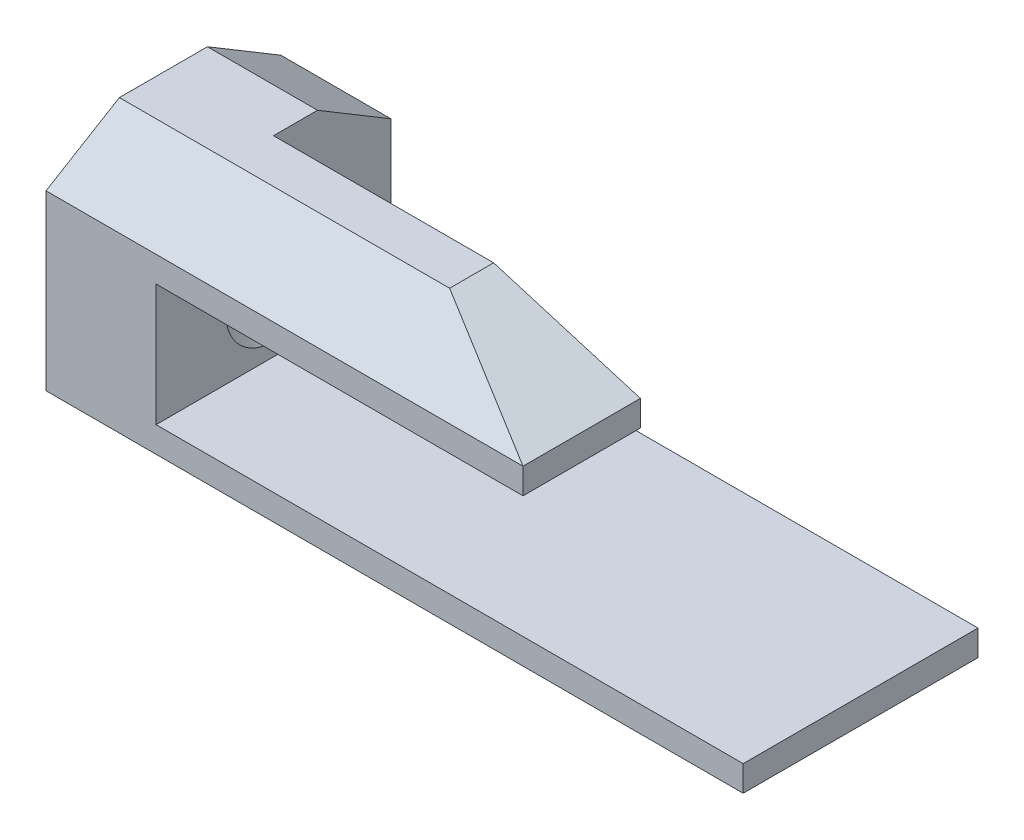
SolidWorks part; units mm, degrees
ref_plane "Спереди" through (0, 0, 0) normal (0, 0, 1) x (1, 0, 0)
ref_plane "Сверху" through (0, 0, 0) normal (0, 1, 0) x (1, 0, 0)
ref_plane "Справа" through (0, 0, 0) normal (1, 0, 0) x (0, 0, -1)
sketch "Эскиз2" plane through (0, 0, 0) normal (0, 0, 1) x (1, 0, 0)
  line L0 (0, 0) -> (65, 0)
  line L1 (65, 0) -> (65, -6)
  line L2 (65, -6) -> (15, -6)
  line L3 (15, -6) -> (15, -22.6)
  line L4 (15, -22.6) -> (95, -22.6)
  line L5 (95, -22.6) -> (95, -28.6)
  line L6 (95, -28.6) -> (0, -28.6)
  line L7 (0, -28.6) -> (0, 0)
  dimension "D1" = 15
  dimension "D2" = 80
  dimension "D3" = 50
  dimension "D4" = 6
  dimension "D5" = 16.6
  dimension "D6" = 6
  dimension "D7" = 65
  dimension "D8" = 95
  dimension "D9" = 28.6
extrude "Бобышка-Вытянуть1" add sketch "Эскиз2" along normal blind 32
sketch "Эскиз3" plane through (0, 0, 0) normal (-1, 0, 0) x (0, 0, 1)
  line L0 (0, 0) -> (32, -28.6) construction
  line L1 (32, -28.6) -> (0, -28.6) construction
  line L2 (32, 0) -> (32, -28.6) construction
  line L3 (32, 0) -> (0, -28.6) construction
  line L4 (32, 0) -> (0, 0) construction
  line L5 (0, -14.3) -> (32, -14.3) construction
  line L6 (0, 0) -> (0, -28.6) construction
  line L7 (16, 0) -> (16, -28.6) construction
  line L9 (5.3934, -14.3) -> (16, -24.9066)
  line L10 (16, -24.9066) -> (26.6066, -14.3)
  line L11 (26.6066, -14.3) -> (16, -3.6934)
  line L12 (16, -3.6934) -> (5.3934, -14.3)
  circle A0 centre (16, -14.3) radius 7.5 construction
  dimension "D1" = 15
extrude "Вырез-Вытянуть2" cut sketch "Эскиз3" against normal blind 3
sketch "Эскиз4" plane through (0, 0, 0) normal (-1, 0, 0) x (0, 0, 1)
  line L0 (16, 0) -> (16, -28.6) construction
  line L1 (32, 0) -> (0, 0) construction
  line L2 (32, -28.6) -> (0, -28.6) construction
  line L3 (32, -14.3) -> (0, -14.3) construction
  line L4 (32, 0) -> (32, -28.6) construction
  line L5 (0, 0) -> (0, -28.6) construction
  circle A0 centre (16, -14.3) radius 2.5
  dimension "D1" = 5
extrude "Вырез-Вытянуть3" cut sketch "Эскиз4" against normal up to surface (15 mm away) up to face at (15, -14.3, 16)
chamfer "Фаска2" distance 4 angle 45 1 edges at (15, -16.8, 16)
sketch "Эскиз6" plane through (65, 0, 0) normal (1, 0, 0) x (0, 0, -1)
  line L2 (-32, 0) -> (0, 0) construction
  line L3 (-16, 0) -> (-22, 0)
  line L4 (-16, 0) -> (-16, 3.5)
  line L5 (-16, 3.5) -> (-22, 3.5)
  line L6 (-22, 0) -> (-22, 3.5)
  line L7 (-32, -6) -> (0, -6) construction
  dimension "D1" = 6
  dimension "D2" = 9.5
extrude "Бобышка-Вытянуть2" add sketch "Эскиз6" against normal up to surface (50 mm away) up to face at (15, -20.8, 16)
sketch "Эскиз7" plane through (65, 0, 0) normal (1, 0, 0) x (0, 0, -1)
  line L1 (-16, 0) -> (0, 0)
  line L2 (-16, 0) -> (-16, -6)
  line L3 (-16, -6) -> (0, -6)
  line L4 (0, 0) -> (0, -6)
extrude "Вырез-Вытянуть5" cut sketch "Эскиз7" against normal up to surface (50 mm away) up to face at (15, -20.8, 16)
sketch "Эскиз8" plane through (15, 0, 0) normal (-1, 0, 0) x (0, 0, 1)
  line L1 (16, 3.5) -> (22, 3.5)
  line L2 (16, 3.5) -> (16, 0)
  line L3 (16, 0) -> (22, 0)
  line L4 (22, 3.5) -> (22, 0)
extrude "Бобышка-Вытянуть3" add sketch "Эскиз8" along normal up to surface (15 mm away) up to face at (0, -14.3, 16)
sketch "Эскиз9" plane through (0, 0, 16) normal (0, 0, -1) x (-1, 0, 0)
  line L1 (0, 3.5) -> (-15, 3.5)
  line L2 (0, 3.5) -> (0, 0)
  line L3 (0, 0) -> (-15, 0)
  line L4 (-15, 3.5) -> (-15, 0)
extrude "Бобышка-Вытянуть4" add sketch "Эскиз9" along normal blind 6
sketch "Эскиз10" plane through (0, 0, 0) normal (-1, 0, 0) x (0, 0, 1)
  line L0 (32, -28.6) -> (0, -28.6) construction
  line L1 (16, -28.6) -> (22, -28.6)
  line L2 (16, -28.6) -> (16, -32.1)
  line L3 (16, -32.1) -> (22, -32.1)
  line L4 (22, -28.6) -> (22, -32.1)
  line L6 (16, -32.1) -> (10, -32.1)
  line L7 (16, -32.1) -> (16, -28.6)
  line L8 (16, -28.6) -> (10, -28.6)
  line L9 (10, -32.1) -> (10, -28.6)
  line M10 (0, -28.6) -> (32, -28.6)
  dimension "D1" = 6
  dimension "D2" = 3.5
  dimension "D3" = 6
  dimension "D4" = 3.5
extrude "Бобышка-Вытянуть5" add sketch "Эскиз10" against normal up to surface (95 mm away) contours L9 L6 L2 M10 | L4 L2 L3 M10 up to face at (95, -25.6, 16)
sketch "Эскиз11" plane through (0, 0, 0) normal (0, 1, 0) x (1, 0, 0)
  line L1 (0, -32) -> (65, -32)
  line L2 (0, -32) -> (0, -22)
  line L3 (0, -22) -> (65, -22)
  line L4 (65, -32) -> (65, -22)
  line L5 (0, 0) -> (15, 0)
  line L6 (0, 0) -> (0, -10)
  line L7 (0, -10) -> (15, -10)
  line L8 (15, 0) -> (15, -10)
extrude "Вырез-Вытянуть6" cut sketch "Эскиз11" against normal blind 2.5
sketch "Эскиз12" plane through (0, -28.6, 0) normal (0, -1, 0) x (1, 0, 0)
  line L1 (0, 0) -> (95, 0)
  line L2 (0, 0) -> (0, 10)
  line L3 (0, 10) -> (95, 10)
  line L4 (95, 0) -> (95, 10)
  line L5 (0, 22) -> (95, 22)
  line L6 (0, 22) -> (0, 32)
  line L7 (0, 32) -> (95, 32)
  line L8 (95, 22) -> (95, 32)
extrude "Вырез-Вытянуть7" cut sketch "Эскиз12" against normal blind 2.5
sketch "Эскиз13" plane through (0, 0, 0) normal (-1, 0, 0) x (0, 0, 1)
  line L0 (0, -26.1) -> (10, -32.1)
  line L1 (10, -32.1) -> (10, -26.1)
  line L2 (10, -26.1) -> (0, -26.1)
  line L3 (22, -26.1) -> (22, -32.1)
  line L4 (22, -32.1) -> (32, -26.1)
  line L5 (32, -26.1) -> (22, -26.1)
extrude "Бобышка-Вытянуть6" add sketch "Эскиз13" against normal up to surface (95 mm away) up to face at (95, -26.725, 16)
sketch "Эскиз14" plane through (0, 0, 0) normal (-1, 0, 0) x (0, 0, 1)
  line L0 (22, 3.5) -> (32, -2.5)
  line L1 (32, -2.5) -> (22, -2.5)
  line L2 (22, -2.5) -> (22, 3.5)
extrude "Бобышка-Вытянуть7" add sketch "Эскиз14" against normal up to surface (65 mm away) up to face at (65, -1.6667, 23.3333)
sketch "Эскиз15" plane through (0, 0, 0) normal (-1, 0, 0) x (0, 0, 1)
  line L0 (10, 3.5) -> (10, -2.5)
  line L1 (10, -2.5) -> (0, -2.5)
  line L2 (0, -2.5) -> (10, 3.5)
extrude "Бобышка-Вытянуть8" add sketch "Эскиз15" against normal up to surface (15 mm away) up to face at (15, -20.8, 16)
sketch "Эскиз16" plane through (0, 0, 32) normal (0, 0, 1) x (1, 0, 0)
  line L0 (65, -2.5) -> (65, 3.5)
  line L1 (65, 3.5) -> (45, 3.5)
  line L2 (0, 3.5) -> (65, 3.5) construction
  line L3 (45, 3.5) -> (65, -2.5)
  line L4 (95, -26.1) -> (95, -32.1)
  line L5 (95, -32.1) -> (75, -32.1)
  line L6 (95, -32.1) -> (0, -32.1) construction
  line L7 (75, -32.1) -> (95, -26.1)
  dimension "D1" = 20
  dimension "D2" = 20
extrude "Вырез-Вытянуть9" cut sketch "Эскиз16" against normal up to surface (32 mm away)
